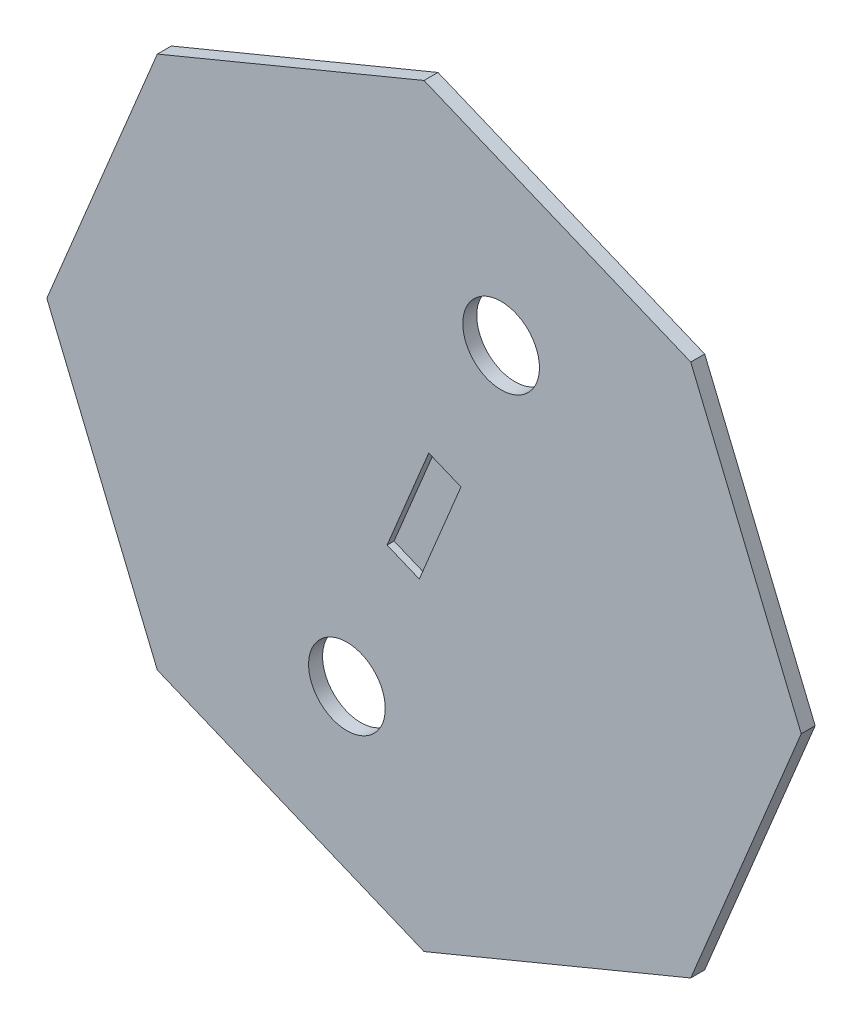
SolidWorks part; units mm, degrees
ref_plane "Front Plane" through (0, 0, 0) normal (0, 0, 1) x (1, 0, 0)
ref_plane "Top Plane" through (0, 0, 0) normal (0, 1, 0) x (1, 0, 0)
ref_plane "Right Plane" through (0, 0, 0) normal (1, 0, 0) x (0, 0, -1)
sketch "Sketch1" plane through (0, 0, 0) normal (0, 0, 1) x (1, 0, 0)
  line L0 (0, -108.2392) -> (76.5367, -76.5367)
  line L1 (108.2392, 0) -> (76.5367, 76.5367)
  line L2 (76.5367, 76.5367) -> (0, 108.2392)
  line L3 (0, 108.2392) -> (-76.5367, 76.5367)
  line L4 (-76.5367, 76.5367) -> (-108.2392, 0)
  line L5 (-108.2392, 0) -> (-76.5367, -76.5367)
  line L6 (-76.5367, -76.5367) -> (0, -108.2392)
  line L7 (76.5367, -76.5367) -> (108.2392, 0)
  circle A0 centre (0, 0) radius 100 construction
  dimension "D1" = 200
extrude "Boss-Extrude1" add sketch "Sketch1" along normal blind 4
sketch "Sketch2" plane through (0, 0, 4) normal (0, 0, 1) x (1, 0, 0)
  line L0 (-76.5367, 76.5367) -> (108.2392, 0)
  line L1 (108.2392, 0) -> (76.5367, -76.5367)
  line L2 (76.5367, -76.5367) -> (-108.2392, 0)
  line L3 (-15.8513, -38.2683) -> (-5.9788, -14.4341)
  line L4 (-10.5982, -12.5207) -> (1.3594, 16.3475)
  line L5 (-10.5982, -12.5207) -> (-1.3594, -16.3475)
  line L6 (1.3594, 16.3475) -> (10.5982, 12.5207)
  line L7 (-1.3594, -16.3475) -> (10.5982, 12.5207)
  line L10 (5.9788, 14.4341) -> (15.8513, 38.2683)
  point P11 (0, 0)
extrude "Cut-Extrude1" cut sketch "Sketch2" against normal blind 2 contours L5 L7 L6 L4
sketch "Sketch3" plane through (0, 0, 4) normal (0, 0, 1) x (1, 0, 0)
  line L0 (5.9788, 14.4341) -> (17.9141, 43.2484)
  line L4 (1.3594, 16.3475) -> (10.5982, 12.5207) construction
  line L6 (76.5367, 76.5367) -> (0, 108.2392) construction
  line L7 (-5.9788, -14.4341) -> (-17.9141, -43.2484)
  line L8 (-10.5982, -12.5207) -> (-1.3594, -16.3475) construction
  line L9 (-76.5367, -76.5367) -> (0, -108.2392) construction
  line L10 (-26.3331, -63.5737) -> (-38.2683, -92.388)
  line L11 (26.3331, 63.5737) -> (38.2683, 92.388)
  circle A0 centre (-22.1236, -53.411) radius 11
  circle A1 centre (22.1236, 53.411) radius 11
  dimension "D1" = 22
  dimension "D2" = 22
extrude "Cut-Extrude2" cut sketch "Sketch3" against normal through all contours A0 | A1
